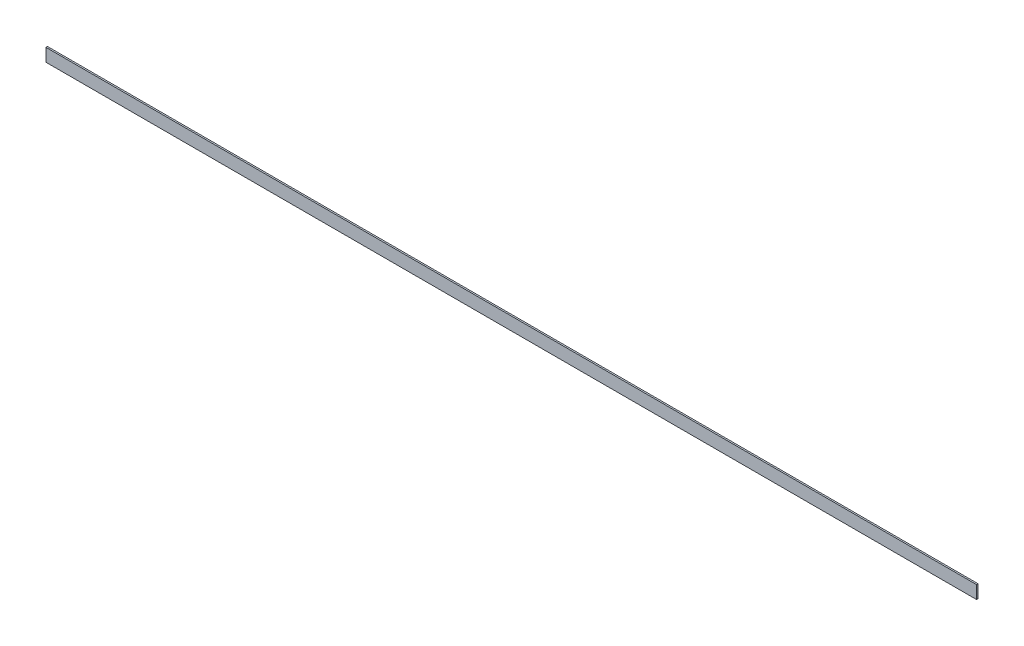
SolidWorks part; units mm, degrees
ref_plane "Plan de face" through (0, 0, 0) normal (0, 0, 1) x (1, 0, 0)
ref_plane "Plan de dessus" through (0, 0, 0) normal (0, 1, 0) x (1, 0, 0)
ref_plane "Plan de droite" through (0, 0, 0) normal (1, 0, 0) x (0, 0, -1)
sketch "Esquisse1" plane through (0, 0, 0) normal (0, 0, 1) x (1, 0, 0)
  line L1 (-499.1039, 236.4821) -> (471.948, 236.4821)
  line L2 (-499.1039, 236.4821) -> (-499.1039, 222.9821)
  line L3 (-499.1039, 222.9821) -> (471.948, 222.9821)
  line L4 (471.948, 236.4821) -> (471.948, 222.9821)
  dimension "D1" = 971.0519
  dimension "D2" = 13.5
extrude "Boss.-Extru.1" add sketch "Esquisse1" along normal blind 1.5875
